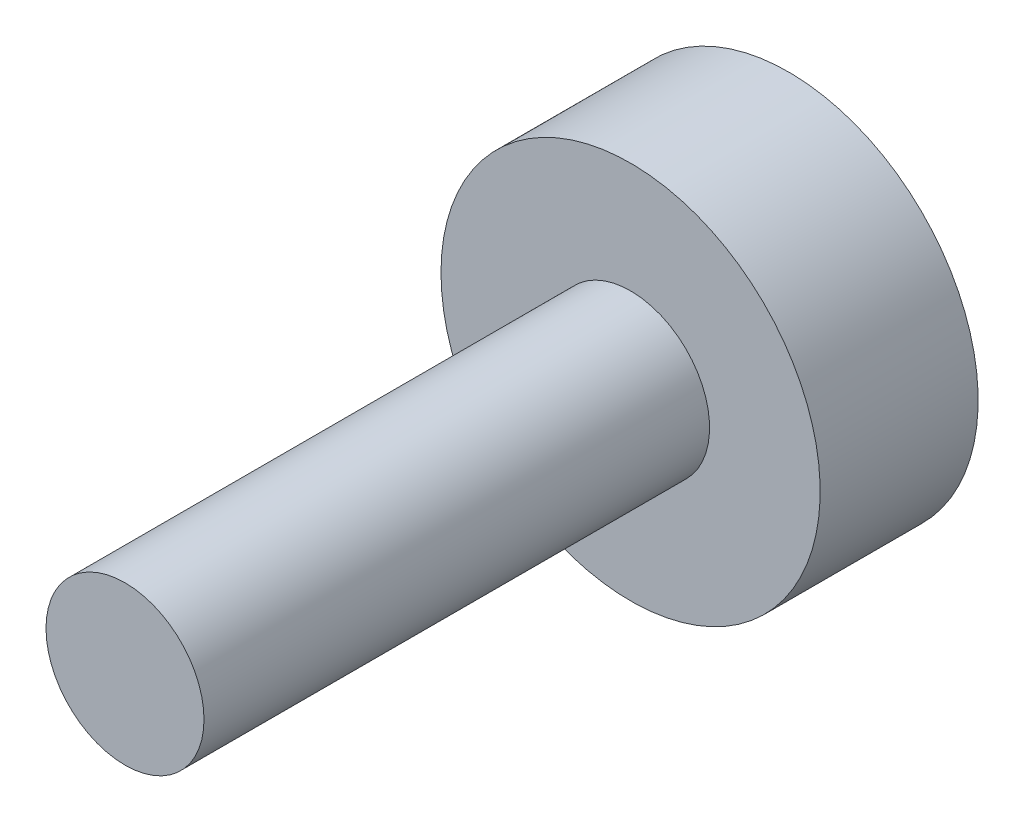
SolidWorks part; units mm, degrees
ref_plane "Front Plane" through (0, 0, 0) normal (0, 0, 1) x (1, 0, 0)
ref_plane "Top Plane" through (0, 0, 0) normal (0, 1, 0) x (1, 0, 0)
ref_plane "Right Plane" through (0, 0, 0) normal (1, 0, 0) x (0, 0, -1)
sketch "Sketch1" plane through (0, 0, 0) normal (0, 0, 1) x (1, 0, 0)
  circle A0 centre (0, 0) radius 2.5
  dimension "D1" = 5
extrude "Boss-Extrude1" add sketch "Sketch1" along normal blind 16
sketch "Sketch2" plane through (0, 0, 0) normal (0, 0, -1) x (-1, 0, 0)
  circle A0 centre (0, 0) radius 6
  dimension "D1" = 12
extrude "Boss-Extrude2" add sketch "Sketch2" along normal blind 5
